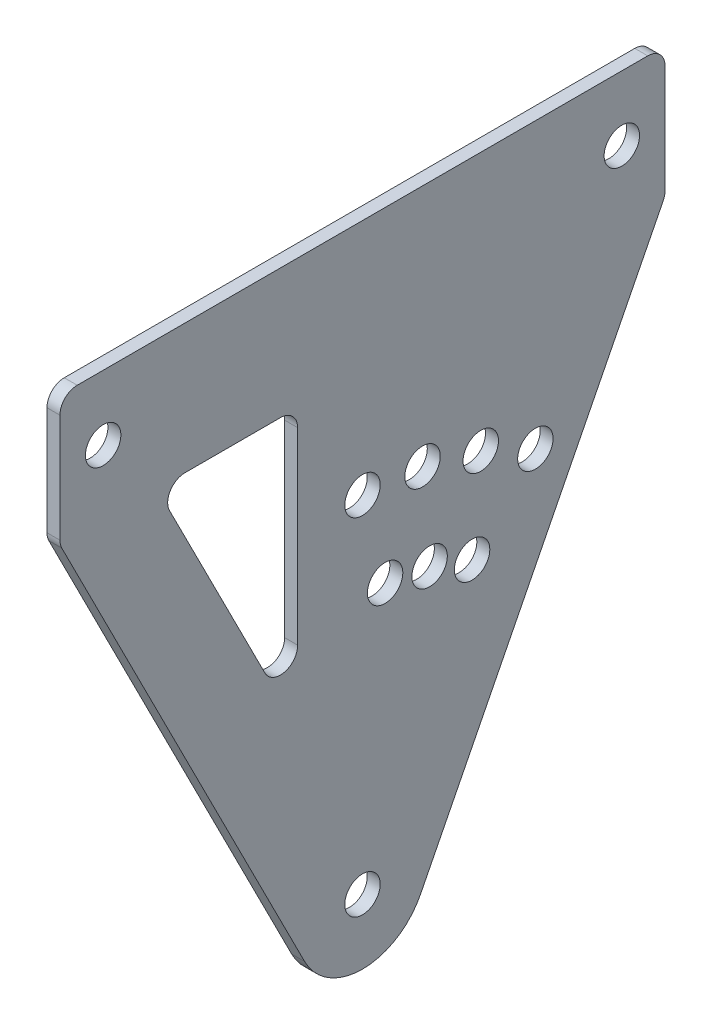
SolidWorks part; units mm, degrees
material "5052-H34"
ref_plane "正面" through (0, 0, 0) normal (0, 0, 1) x (1, 0, 0)
ref_plane "平面" through (0, 0, 0) normal (0, 1, 0) x (1, 0, 0)
ref_plane "右側面" through (0, 0, 0) normal (1, 0, 0) x (0, 0, -1)
sketch "ｽｹｯﾁ1" plane through (0, 0, 0) normal (1, 0, 0) x (0, 0, -1)
  line L0 (0, 0) -> (0, 40) construction
  line L1 (0, 0) -> (0, 40) construction
  line L2 (0, 0) -> (6.9459, 39.3923) construction
  line L3 (0, 0) -> (2.6147, 29.8858) construction
  line L4 (0, 0) -> (2.6147, 29.8858) construction
  line L5 (0, 0) -> (7.7646, 28.9778) construction
  line L6 (0, 0) -> (20, 34.641) construction
  line L7 (0, 60) -> (0, 0) construction
  line L8 (0, 60) -> (-30, 60) construction
  line L10 (-35, 67.5) -> (35, 67.5)
  line L11 (-35, 67.5) -> (-35, 52.5)
  line L13 (35, 67.5) -> (35, 52.5)
  line L14 (-35, 67.5) -> (35, 52.5) construction
  line L15 (-35, 52.5) -> (35, 67.5) construction
  line L17 (35, 52.5) -> (6.6906, -3.389)
  line L18 (-35, 52.5) -> (-6.6906, -3.389)
  line L19 (35, 52.5) -> (-35, 52.5) construction
  line L20 (-26.0791, 57.0187) -> (2.2302, 1.1297)
  line L21 (-5, 0) -> (-5, 40)
  line L22 (-7.5, 60) -> (-7.5, 0)
  line L23 (-7.5, 52.5) -> (-23.7903, 52.5)
  circle A0 centre (0, 0) radius 2.05
  circle A1 centre (0, 40) radius 2.05
  circle A2 centre (6.9459, 39.3923) radius 2.05
  circle A3 centre (13.6808, 37.5877) radius 2.05
  circle A4 centre (20, 34.641) radius 2.05
  circle A5 centre (2.6147, 29.8858) radius 2.05
  circle A6 centre (7.7646, 28.9778) radius 2.05
  circle A7 centre (12.6785, 27.1892) radius 2.05
  circle A8 centre (-30, 60) radius 2.05
  circle A9 centre (30, 60) radius 2.05
  arc A11 (-6.6906, -3.389) -> (6.6906, -3.389) centre (0, 0) ccw
  arc A12 (0, 7.5) -> (-6.6906, -3.389) centre (0, 0) ccw construction
  arc A13 (6.6906, -3.389) -> (3.75, 6.4952) centre (0, 0) ccw construction
  arc A14 (3.75, 6.4952) -> (0, 7.5) centre (0, 0) ccw
  dimension "D1" = 4.1
  dimension "D10" = 4.1
  dimension "D15" = 5
  dimension "D16" = 15
  dimension "D2" = 40
  dimension "D4" = 10
  dimension "D5" = 5
  dimension "D6" = 30
  dimension "D8" = 10
  dimension "D9" = 30
  dimension "D11" = 60
  dimension "D12" = 60
  dimension "D13" = 15
  dimension "D14" = 5
  dimension "D17" = 12.5
  dimension "D18" = 10
  dimension "D19" = 5
  dimension "D20" = 7.5
  dimension "D3" = 4
  dimension "D7" = 3
extrude "ﾎﾞｽ - 押し出し1" add sketch "ｽｹｯﾁ1" along normal blind 1.5
fillet "ﾌｨﾚｯﾄ2" radius 2 7 edges at (0.75, 52.5, 7.5) (0.75, 20.3393, 7.5) (0.75, 52.5, 23.7903) (0.75, 67.5, -35) (0.75, 52.5, -35) (0.75, 52.5, 35) (0.75, 67.5, 35)
